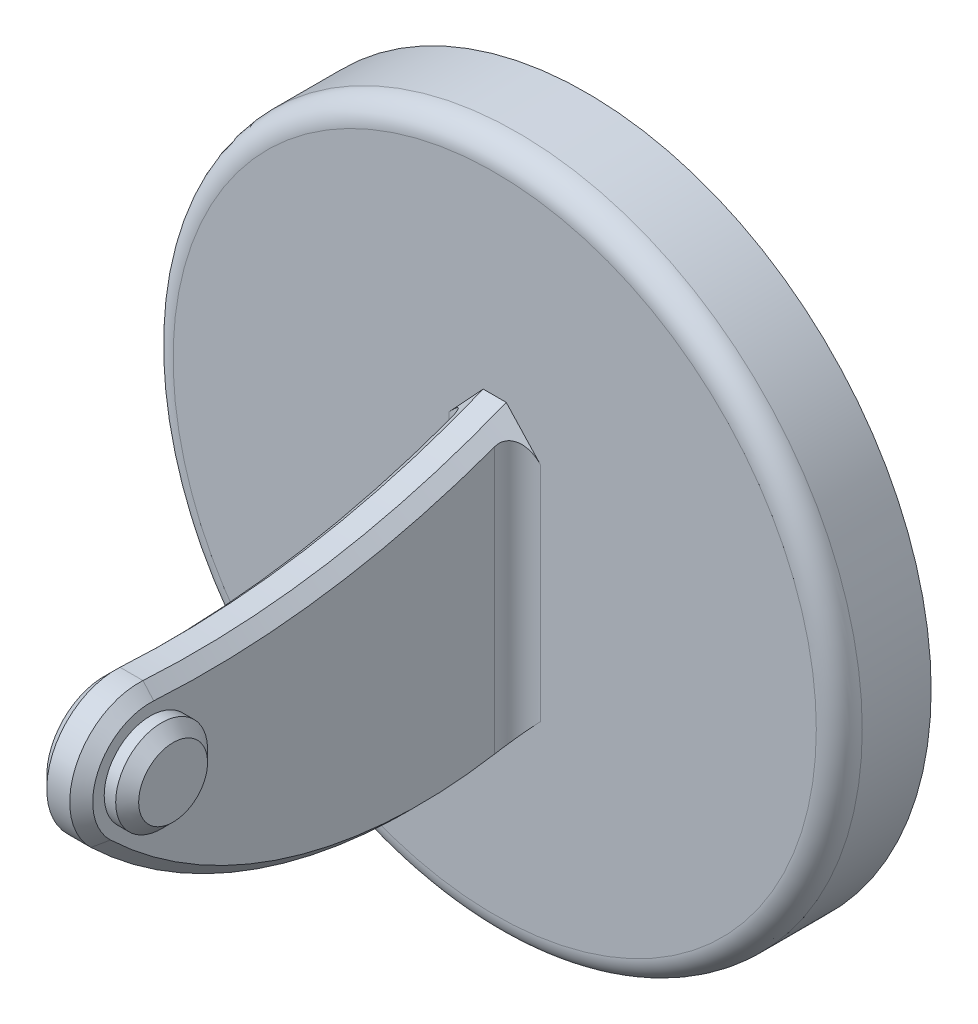
SolidWorks part; units mm, degrees
ref_plane "Front Plane" through (0, 0, 0) normal (1, 0, 0) x (0, 1, 0)
ref_plane "Top Plane" through (0, 0, 0) normal (0, 0, 1) x (0, 1, 0)
ref_plane "Right Plane" through (0, 0, 0) normal (0, 1, 0) x (-1, 0, 0)
sketch "Sketch1" plane through (0, 0, 0) normal (0, 0, 1) x (0, 1, 0)
  circle A0 centre (0, 0) radius 75
  dimension "D1" = 150
extrude "Boss-Extrude1" add sketch "Sketch1" along normal blind 20
fillet "Fillet1" radius 5 1 edges at (75, 0, 20)
sketch "Sketch2" plane through (0, 0, 0) normal (1, 0, 0) x (0, 1, 0)
  line L0 (0, 0) -> (0, 100) construction
  line L1 (-35, 15) -> (30, 15)
  line L2 (-75, 15) -> (75, 15) construction
  arc A1 (14.9706, 99.062) -> (-10.8492, 110.3583) centre (0, 100) ccw
  arc A2 (-10.8492, 110.3583) -> (-35, 15) centre (61.4788, 41.3028) ccw
  arc A3 (14.9706, 99.062) -> (30, 15) centre (194.6184, 87.8065) ccw
  dimension "D4" = 30
  dimension "D5" = 180
  dimension "D6" = 100
  dimension "D1" = 30
  dimension "D2" = 35
  dimension "D3" = 100
extrude "Boss-Extrude2" add sketch "Sketch2" along normal mid plane 10 contours A1 A2 L1 A3
chamfer "Chamfer1" distance 2.5 angle 45 6 edges at (-5, -34.7965, 68.3412) (-5, 6.0123, 113.7423) (-5, 16.9703, 58.8038) (5, -34.7965, 68.3412) (5, 6.0123, 113.7423) (5, 16.9703, 58.8038)
fillet "Fillet2" radius 5 2 edges at (-5, -4.2415, 20) (5, -4.2415, 20)
sketch "Sketch3" plane through (5, 0, 0) normal (1, 0, 0) x (0, 1, 0)
  circle A0 centre (0, 100) radius 10
  dimension "D1" = 20
extrude "Boss-Extrude4" add sketch "Sketch3" along normal blind 5
chamfer "Chamfer3" distance 2.5 angle 45 1 edges at (10, 0, 90)
sketch "Sketch4" plane through (-5, 0, 0) normal (-1, 0, 0) x (0, -1, 0)
  circle A0 centre (0, 100) radius 5
extrude "Cut-Extrude1" cut sketch "Sketch4" against normal blind 10
